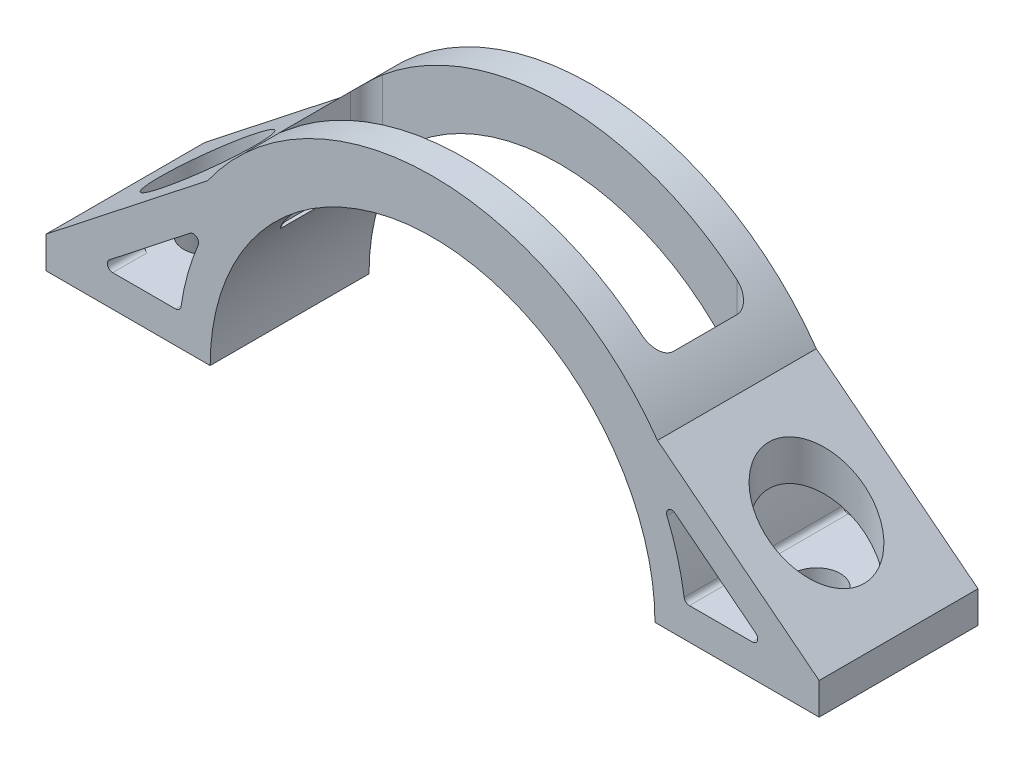
SolidWorks part; units mm, degrees
material "Acrílico (Impacto medio-alto)"
ref_plane "Alzado" through (0, 0, 0) normal (0, 0, 1) x (1, 0, 0)
ref_plane "Planta" through (0, 0, 0) normal (0, 1, 0) x (1, 0, 0)
ref_plane "Vista lateral" through (0, 0, 0) normal (1, 0, 0) x (0, 0, -1)
sketch "Croquis1" plane through (0, 0, 0) normal (0, 0, 1) x (1, 0, 0)
  line L0 (-26, 0) -> (-21, 0)
  line L5 (21, 0) -> (26, 0)
  arc A0 (26, 0) -> (-26, 0) centre (0, 0) ccw
  arc A2 (21, 0) -> (-21, 0) centre (0, 0) ccw
  point P0 (0, 0)
  dimension "D3" = 21
  dimension "D2" = 26
  dimension "D1" = 52
extrude "Saliente-Extruir1" add sketch "Croquis1" along normal mid plane 15
sketch "Croquis2" plane through (0, 0, 0) normal (0, 0, 1) x (1, 0, 0)
  line L0 (26, 0) -> (36.5, 0)
  line L1 (36.5, 0) -> (36.5, 3)
  line L2 (36.5, 3) -> (21.2368, 15)
  arc A0 (26, 0) -> (-26, 0) centre (0, 0) ccw construction
  arc A1 (26, 0) -> (21.2368, 15) centre (0, 0) ccw
  dimension "D1" = 10.5
  dimension "D2" = 3
  dimension "D3" = 15
extrude "Saliente-Extruir2" add sketch "Croquis2" along normal mid plane 15
sketch "Croquis3" plane through (0, 0, 0) normal (0, -1, 0) x (1, 0, 0)
  line L0 (21, -7.5) -> (36.5, -7.5) construction
  line L1 (36.5, 7.5) -> (36.5, -7.5) construction
  circle A0 centre (28.75, 0) radius 2.25
  dimension "D3" = 4.5
  dimension "D1" = 7.5
  dimension "D2" = 7.75
extrude "Cortar-Extruir1" cut sketch "Croquis3" against normal through all
ref_plane "Plano1" through (0, 3, 0) normal (0, -1, 0) x (-1, 0, 0)
sketch "Croquis4" plane through (0, 3, 0) normal (0, -1, 0) x (-1, 0, 0)
  circle A0 centre (-28.75, 0) radius 4.5
  dimension "D1" = 9
extrude "Cortar-Extruir2" cut sketch "Croquis4" against normal through all
mirror "Simetría1" about plane through (0, 0, 0) normal (1, 0, 0) of "Saliente-Extruir2"
sketch "Croquis6" plane through (0, 0, 7.5) normal (0, 0, 1) x (1, 0, 0)
  line L5 (33.5, 0) -> (33.5, 1.5425)
  line L6 (33.5, 1.5425) -> (19.3826, 12.6416)
  line L8 (30.5102, 3.8931) -> (22.8989, 9.877)
  line L10 (23.8118, 3) -> (36.5, 3)
  line L11 (24.2487, 3) -> (30.2011, 3)
  arc A1 (23.7538, 3.4286) -> (24.2487, 3) centre (24.2487, 3.5) ccw
  arc A2 (23.8118, 3) -> (-24, 0) centre (0, 0) ccw
  arc A3 (23.7538, 3.4286) -> (22.1289, 9.2904) centre (0, 0) ccw
  arc A4 (22.1289, 9.2904) -> (22.8989, 9.877) centre (22.5899, 9.484) cw
  arc A5 (30.2011, 3) -> (30.5102, 3.8931) centre (30.2011, 3.5) ccw
  dimension "D3" = 0.5
  dimension "D4" = 0.5
  dimension "D1" = 3
  dimension "D2" = 3
extrude "Cortar-Extruir3" cut sketch "Croquis6" against normal through all
ref_plane "Plano2" through (0, 26, 0) normal (0, 1, 0) x (1, 0, 0)
sketch "Croquis8" plane through (0, 26, 0) normal (0, 1, 0) x (1, 0, 0)
  line L17 (-18.2368, -4.5) -> (18.2368, -4.5)
  line L18 (18.2368, -4.5) -> (18.2368, 4.5)
  line L19 (-18.2368, 4.5) -> (-18.2368, -4.5)
  line L20 (18.2368, 4.5) -> (-18.2368, 4.5)
  line L21 (-16.7368, -4.5) -> (16.7368, -4.5)
  line L22 (18.2368, -3) -> (18.2368, 3)
  line L23 (-18.2368, 3) -> (-18.2368, -3)
  line L24 (16.7368, 4.5) -> (-16.7368, 4.5)
  arc A0 (-16.7368, -4.5) -> (-18.2368, -3) centre (-16.7368, -3) cw
  arc A1 (-18.2368, 3) -> (-16.7368, 4.5) centre (-16.7368, 3) cw
  arc A2 (18.2368, 3) -> (16.7368, 4.5) centre (16.7368, 3) ccw
  arc A3 (16.7368, -4.5) -> (18.2368, -3) centre (16.7368, -3) ccw
  dimension "D2" = 1.5
  dimension "D1" = 3
extrude "Cortar-Extruir4" cut sketch "Croquis8" against normal blind 15
mirror "Simetría2" about plane through (0, 0, 0) normal (1, 0, 0) of "Cortar-Extruir1", "Cortar-Extruir3", "Cortar-Extruir2"
